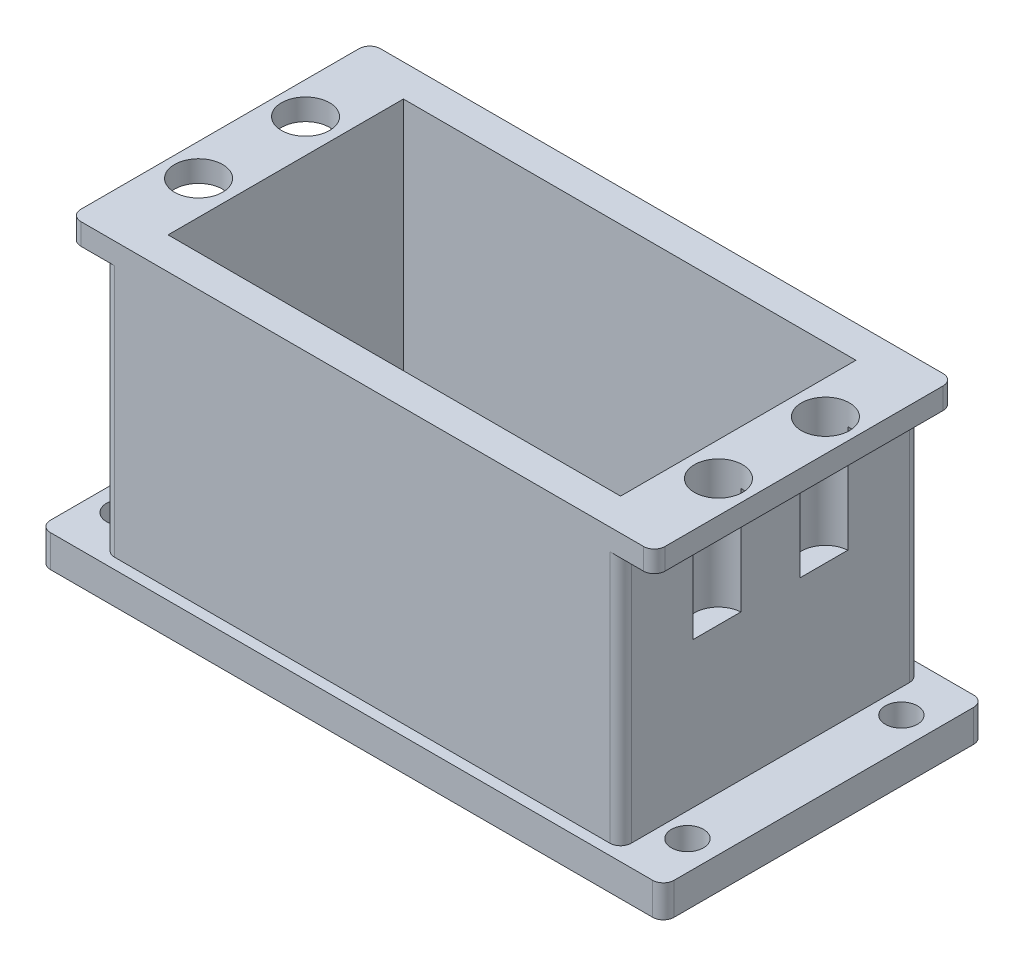
SolidWorks part; units mm, degrees
ref_plane "Front Plane" through (0, 0, 0) normal (0, 0, 1) x (1, 0, 0)
ref_plane "Top Plane" through (0, 0, 0) normal (0, 1, 0) x (1, 0, 0)
ref_plane "Right Plane" through (0, 0, 0) normal (1, 0, 0) x (0, 0, -1)
sketch "Sketch1" plane through (0, 0, 0) normal (0, 1, 0) x (1, 0, 0)
  line L0 (-21.15, 11) -> (21.15, 11)
  line L1 (-20.15, 10) -> (20.15, 10) construction
  line L2 (-20.15, 10) -> (-20.15, -10) construction
  line L3 (-20.15, -10) -> (20.15, -10) construction
  line L4 (20.15, 10) -> (20.15, -10) construction
  line L5 (-20.15, 10) -> (20.15, -10) construction
  line L6 (-20.15, -10) -> (20.15, 10) construction
  line L7 (21.15, 11) -> (21.15, -11)
  line L8 (-21.15, -11) -> (21.15, -11)
  line L9 (-21.15, 11) -> (-21.15, -11)
  line L10 (-24.15, 14) -> (24.15, 14)
  line L11 (24.15, 14) -> (24.15, -14)
  line L12 (-24.15, -14) -> (24.15, -14)
  line L13 (-24.15, 14) -> (-24.15, -14)
  point P0 (0, 0)
  dimension "D1" = 20
  dimension "D2" = 40.3
  dimension "D3" = 1
  dimension "D4" = 3
extrude "Boss-Extrude1" add sketch "Sketch1" along normal blind 26.6
sketch "Sketch2" plane through (0, 26.6, 0) normal (0, 1, 0) x (1, 0, 0)
  line L0 (21.15, 11) -> (-21.15, 11) construction
  line L1 (21.15, 11) -> (-21.15, 11)
  line L2 (21.15, -11) -> (21.15, 11) construction
  line L3 (-21.15, -11) -> (21.15, -11) construction
  line L5 (-27.3, 14) -> (27.3, 14)
  line L7 (-27.3, 14) -> (-27.3, -14)
  line L12 (-21.15, 11) -> (-21.15, -11) construction
  line L13 (21.15, -11) -> (21.15, 11)
  line L14 (-21.15, -11) -> (21.15, -11)
  line L15 (-21.15, 11) -> (-21.15, -11)
  line L16 (-27.3, -14) -> (27.3, -14)
  line L17 (27.3, 14) -> (27.3, -14)
  line L18 (-27.3, 14) -> (27.3, -14) construction
  line L19 (-27.3, -14) -> (27.3, 14) construction
  point P0 (0, 0)
  dimension "D1" = 54.6
  dimension "D2" = 28
extrude "Boss-Extrude2" add sketch "Sketch2" along normal blind 2
sketch "Sketch3" plane through (0, 0, 0) normal (0, -1, 0) x (1, 0, 0)
  line L4 (-24.15, 14) -> (-24.15, -14)
  line L6 (-24.15, 14) -> (-24.15, -14)
  line L12 (-24.15, -14) -> (24.15, -14)
  line L13 (-24.15, -14) -> (24.15, -14)
  line L14 (24.15, -14) -> (24.15, 14)
  line L15 (24.15, -14) -> (24.15, 14)
  line L16 (24.15, 14) -> (-24.15, 14)
  line L17 (24.15, 14) -> (-24.15, 14)
  dimension "D1" = 0
sketch "Sketch4" plane through (0, 28.6, 0) normal (0, 1, 0) x (1, 0, 0)
  line L1 (-24.3, 5) -> (24.3, 5) construction
  line L2 (-24.3, 5) -> (-24.3, -5) construction
  line L3 (-24.3, -5) -> (24.3, -5) construction
  line L4 (24.3, 5) -> (24.3, -5) construction
  line L5 (-24.3, 5) -> (24.3, -5) construction
  line L6 (-24.3, -5) -> (24.3, 5) construction
  line L7 (27.3, 14) -> (-27.3, 14) construction
  circle A0 centre (-24.3, 5) radius 2.25
  circle A1 centre (-24.3, -5) radius 2.25
  circle A2 centre (24.3, 5) radius 2.25
  circle A3 centre (24.3, -5) radius 2.25
  point P0 (0, 0)
  dimension "D3" = 4.5
  dimension "D1" = 48.6
  dimension "D2" = 9
extrude "Cut-Extrude1" cut sketch "Sketch4" against normal blind 12
sketch "Sketch5" plane through (0, 0, 0) normal (0, -1, 0) x (1, 0, 0)
  line L4 (-24.15, 14) -> (-24.15, -14)
  line L13 (-29.15, 15) -> (29.15, 15)
  line L14 (-29.15, 15) -> (-29.15, -15)
  line L15 (-29.15, -15) -> (29.15, -15)
  line L16 (29.15, 15) -> (29.15, -15)
  line L17 (-29.15, 15) -> (29.15, -15) construction
  line L18 (-29.15, -15) -> (29.15, 15) construction
  line L62 (-24.15, 14) -> (-24.15, -14)
  line L74 (-24.15, -14) -> (24.15, -14)
  line L76 (-24.15, -14) -> (24.15, -14)
  line L78 (24.15, -14) -> (24.15, 14)
  line L82 (24.15, -14) -> (24.15, 14)
  line L86 (24.15, 14) -> (-24.15, 14)
  line L88 (24.15, 14) -> (-24.15, 14)
  point P2 (0, 0)
  dimension "D1" = 0
extrude "Boss-Extrude3" add sketch "Sketch5" against normal blind 3
sketch "Sketch6" plane through (-29.15, 0, 0) normal (-1, 0, 0) x (0, 0, 1)
  line L0 (15, 0) -> (-15, 0) construction
  line L1 (-5, -12) -> (5, -12)
  line L2 (-5, -12) -> (-5, 12)
  line L3 (-5, 12) -> (5, 12)
  line L4 (5, -12) -> (5, 12)
  line L5 (-5, -12) -> (5, 12) construction
  line L6 (-5, 12) -> (5, -12) construction
  point P0 (0, 0)
  dimension "D1" = 12
  dimension "D2" = 10
extrude "Cut-Extrude2" cut sketch "Sketch6" against normal blind 10
sketch "Sketch7" plane through (0, 0, 0) normal (0, -1, 0) x (1, 0, 0)
  line L0 (29.15, 15) -> (-29.15, 15) construction
  line L1 (-26.4, 10) -> (26.4, 10) construction
  line L2 (-26.4, 10) -> (-26.4, -10) construction
  line L3 (-26.4, -10) -> (26.4, -10) construction
  line L4 (26.4, 10) -> (26.4, -10) construction
  line L5 (-26.4, 10) -> (26.4, -10) construction
  line L6 (-26.4, -10) -> (26.4, 10) construction
  line L7 (29.15, -15) -> (29.15, 15) construction
  circle A0 centre (-26.4, 10) radius 1.5
  circle A1 centre (-26.4, -10) radius 1.5
  circle A2 centre (26.4, 10) radius 1.5
  circle A3 centre (26.4, -10) radius 1.5
  point P0 (0, 0)
  dimension "D3" = 3
  dimension "D1" = 5
  dimension "D2" = 2.75
extrude "Cut-Extrude3" cut sketch "Sketch7" against normal blind 10
fillet "Fillet1" radius 1 4 edges at (24.15, 14.8, 14) (24.15, 14.8, -14) (-24.15, 14.8, -14) (-24.15, 14.8, 14)
fillet "Fillet2" radius 1 10 edges at (-27.3, 27.6, -14) (-27.3, 27.6, 14) (27.3, 27.6, 14) (27.3, 27.6, -14) (29.15, 1.5, 15) (29.15, 1.5, -15) (-29.15, 1.5, -5) (-29.15, 1.5, 15) (-29.15, 1.5, 5) (-29.15, 1.5, -15)
fillet "Fillet3" radius 1 2 edges at (-22.65, 12, -5) (-22.65, 12, 5)
